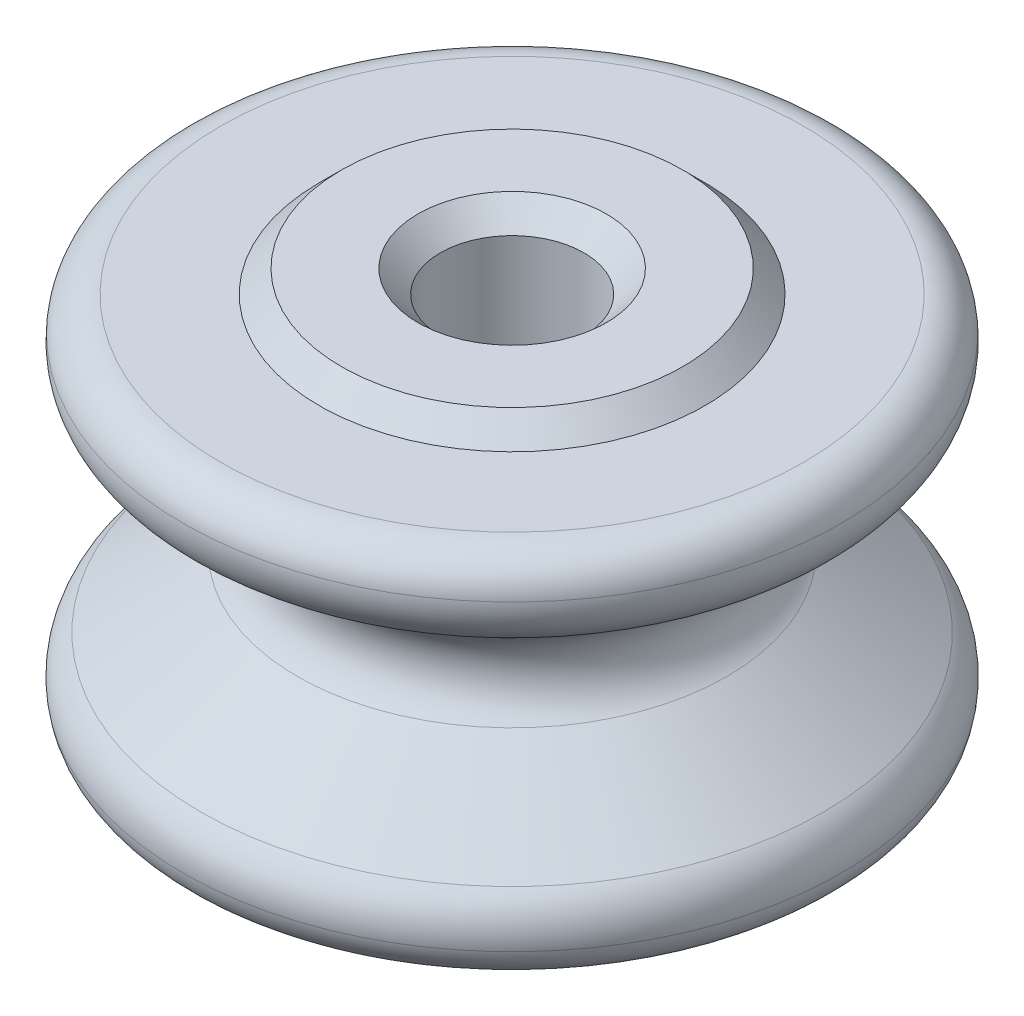
SolidWorks part; units mm, degrees
ref_plane "Płaszczyzna przednia" through (0, 0, 0) normal (0, 0, 1) x (1, 0, 0)
ref_plane "Płaszczyzna górna" through (0, 0, 0) normal (0, 1, 0) x (1, 0, 0)
ref_plane "Płaszczyzna prawa" through (0, 0, 0) normal (1, 0, 0) x (0, 0, -1)
sketch "Szkic1" plane through (0, 0, 0) normal (0, 0, 1) x (1, 0, 0)
  line L1 (1, -17.5) -> (4.4, -17.5)
  line L2 (0, -16.5) -> (1, -17.5)
  line L5 (5.4, -16.5) -> (9.7835, -16.5)
  line L7 (4.4, 1) -> (5.4, 0)
  line L8 (5.4, 0) -> (9.7835, 0)
  line L10 (4.4, -17.5) -> (5.4, -16.5)
  line L11 (0, 0) -> (-3.2, 0)
  line L14 (0, 0) -> (1, 1)
  line L15 (1, 1) -> (4.4, 1)
  line L16 (-3.2, 0) -> (-3.2, -16.5)
  line L17 (-3.2, -16.5) -> (0, -16.5)
  line L19 (10.6728, -13.0485) -> (6.3705, -9.9665)
  line L20 (10.67, -3.4536) -> (6.3488, -6.5091)
  arc A0 (9.7835, -16.5) -> (11.4736, -14.9983) centre (9.7835, -14.7981) ccw
  arc A1 (6.3488, -6.5091) -> (6.3705, -9.9665) centre (7.6679, -8.2296) ccw
  arc A2 (9.7835, 0) -> (11.4736, -1.5017) centre (9.7835, -1.7019) cw
  arc A3 (11.4736, -14.9983) -> (10.6728, -13.0485) centre (9.3207, -14.7432) ccw
  arc A4 (11.4736, -1.5017) -> (10.67, -3.4536) centre (9.3207, -1.7568) cw
  point P1 (0, -17.5)
  point P3 (0, 0)
  point P11 (0, 0)
  point P20 (0, 0)
  point P22 (10.6728, -3.4536)
  point P32 (5.7455, -9.2249)
  point P35 (11.3459, -14.1231)
  point P38 (11.4278, -2.1411)
  dimension "D6" = 5.7455
  dimension "D15" = 11.4278
  dimension "D17" = 3.2
  dimension "D16" = 9.2249
  dimension "D1" = 1.7019
  dimension "D2" = 2.168
  dimension "D7" = 6.3488
  dimension "D12" = 10.67
  dimension "D13" = 10.6728
  dimension "D3" = 1
  dimension "D10" = 6.5091
  dimension "D4" = 9.3207
  dimension "D9" = 7.6679
  dimension "D11" = 4.4
  dimension "D14" = 11.3459
  dimension "D8" = 6.3705
  dimension "D5" = 9.7835
revolve "Obrót1" add sketch "Szkic1" angle 360 about L16
sketch "Szkic5" plane through (0, 0, 0) normal (0, 1, 0) x (1, 0, 0)
  circle A0 centre (-3.2, 0) radius 3.2
  circle A1 centre (-3.2, 0) radius 3.2 construction
  dimension "D1" = 6.4
extrude "Wytnij-wyciągnięcie1" cut sketch "Szkic5" against normal blind 19
